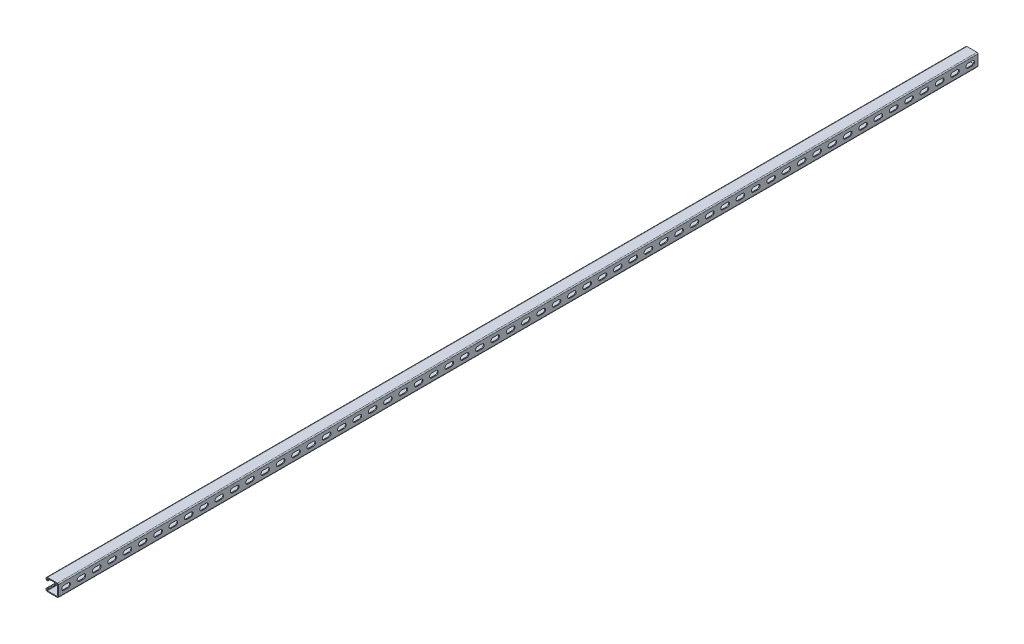
SolidWorks part; units mm, degrees
ref_plane "Front Plane" through (0, 0, 0) normal (0, 0, 1) x (1, 0, 0)
ref_plane "Top Plane" through (0, 0, 0) normal (0, 1, 0) x (1, 0, 0)
ref_plane "Right Plane" through (0, 0, 0) normal (1, 0, 0) x (0, 0, -1)
sketch "Sketch1" plane through (0, 0, 0) normal (0, 0, 1) x (1, 0, 0)
  line L0 (0, 0) -> (-41.275, 0) construction
  line L3 (-41.275, 20.6375) -> (0, 20.6375) construction
  line L4 (-41.275, 20.6375) -> (-41.275, -20.6375) construction
  line L5 (-41.275, -20.6375) -> (0, -20.6375) construction
  line L6 (0, 20.6375) -> (0, -20.6375) construction
  line L7 (-36.2267, 20.6375) -> (-3.4607, 20.6375)
  line L8 (0, 17.1767) -> (0, -17.1767)
  line L9 (-2.794, -17.1767) -> (-2.794, 17.1767)
  line L10 (-3.4608, 17.8435) -> (-36.2267, 17.8435)
  line L11 (-41.275, 15.5892) -> (-41.275, 14.5732)
  line L12 (-37.8142, 11.1125) -> (-35.5346, 11.1125)
  line L14 (-35.5346, 13.9065) -> (-37.8142, 13.9065)
  line L15 (-38.481, 14.5732) -> (-38.481, 15.5892)
  line L16 (-38.481, -14.5733) -> (-38.481, -15.5893)
  line L17 (-35.5346, -13.9065) -> (-37.8142, -13.9065)
  line L18 (-37.8142, -11.1125) -> (-35.5346, -11.1125)
  line L19 (-41.275, -15.5893) -> (-41.275, -14.5733)
  line L20 (-3.4607, -17.8435) -> (-36.2267, -17.8435)
  line L21 (-36.2267, -20.6375) -> (-3.4607, -20.6375)
  line L22 (-2.794, -20.6375) -> (-2.794, 20.6375) construction
  arc A1 (0, 17.1767) -> (-3.4607, 20.6375) centre (-3.4607, 17.1767) ccw
  arc A2 (-2.794, 17.1767) -> (-3.4608, 17.8435) centre (-3.4607, 17.1767) ccw
  arc A4 (-36.2267, 20.6375) -> (-41.275, 15.5892) centre (-36.2267, 15.5892) ccw
  arc A5 (-41.275, 14.5732) -> (-37.8142, 11.1125) centre (-37.8142, 14.5732) ccw
  arc A6 (-35.5346, 11.1125) -> (-35.5346, 13.9065) centre (-35.5346, 12.5095) ccw
  arc A7 (-37.8142, 13.9065) -> (-38.481, 14.5732) centre (-37.8142, 14.5732) cw
  arc A8 (-38.481, 15.5892) -> (-36.2267, 17.8435) centre (-36.2267, 15.5892) cw
  arc A9 (-38.481, -15.5893) -> (-36.2267, -17.8435) centre (-36.2267, -15.5893) ccw
  arc A10 (-37.8142, -13.9065) -> (-38.481, -14.5733) centre (-37.8142, -14.5733) ccw
  arc A11 (-35.5346, -11.1125) -> (-35.5346, -13.9065) centre (-35.5346, -12.5095) cw
  arc A12 (-41.275, -14.5733) -> (-37.8142, -11.1125) centre (-37.8142, -14.5733) cw
  arc A13 (-36.2267, -20.6375) -> (-41.275, -15.5893) centre (-36.2267, -15.5893) cw
  arc A14 (-2.794, -17.1767) -> (-3.4607, -17.8435) centre (-3.4607, -17.1767) cw
  arc A15 (0, -17.1767) -> (-3.4607, -20.6375) centre (-3.4607, -17.1767) cw
  point P24 (0, 20.6375)
  point P65 (-2.794, 0)
  dimension "D1" = 3.4608
  dimension "D2" = 5.0482
  dimension "D3" = 3.4608
  dimension "Ht." = 41.275
  dimension "Wd." = 41.275
  dimension "Thk." = 2.794
  dimension "D4" = 9.525
  dimension "D5" = 7.1374
extrude "Boss-Extrude1" add sketch "Sketch1" against normal blind 3048
sketch "Sketch3" plane through (0, 0, 0) normal (1, 0, 0) x (0, 0, -1)
  line L0 (0, 0) -> (3048, 0) construction
  point P2 (101.6, 0)
  point P3 (2946.4, 0)
  dimension "D1" = 101.6
  dimension "D2" = 101.6
  dimension "D3" = 3048
sketch "Sketch2" plane through (0, 0, 0) normal (1, 0, 0) x (0, 0, -1)
  line L0 (18.2562, 0) -> (32.5437, 0) construction
  line L1 (18.2562, 7.1437) -> (32.5437, 7.1437)
  line L2 (18.2562, -7.1437) -> (32.5437, -7.1437)
  line L3 (18.2562, 0) -> (0, 0) construction
  line L4 (25.4, 0) -> (76.2, 0) construction
  line L5 (0, -17.1767) -> (0, 17.1767) construction
  arc A0 (18.2562, 7.1437) -> (18.2562, -7.1437) centre (18.2562, 0) ccw
  arc A1 (32.5437, -7.1437) -> (32.5437, 7.1437) centre (32.5437, 0) ccw
  point P3 (25.4, 0)
  dimension "Hole to End" = 11.1125
  dimension "D2" = 25.4
extrude "Cut-Extrude1" cut sketch "Sketch2" against normal up to vertex (2.794 mm away) up to point (-2.794, 0, 0)
pattern_linear "LPattern1" count 60 spacing 50.8 along (0, 0, -1) of "Cut-Extrude1"
equation "\"D1@LPattern1\" = \"Slot Ctr.@Sketch2\""
equation "\"Hole Count@LPattern1\" = \"Lg.@Boss-Extrude1\" / \"D1@LPattern1\""
equation "\"D3@Sketch3\" = \"Lg.@Boss-Extrude1\""
